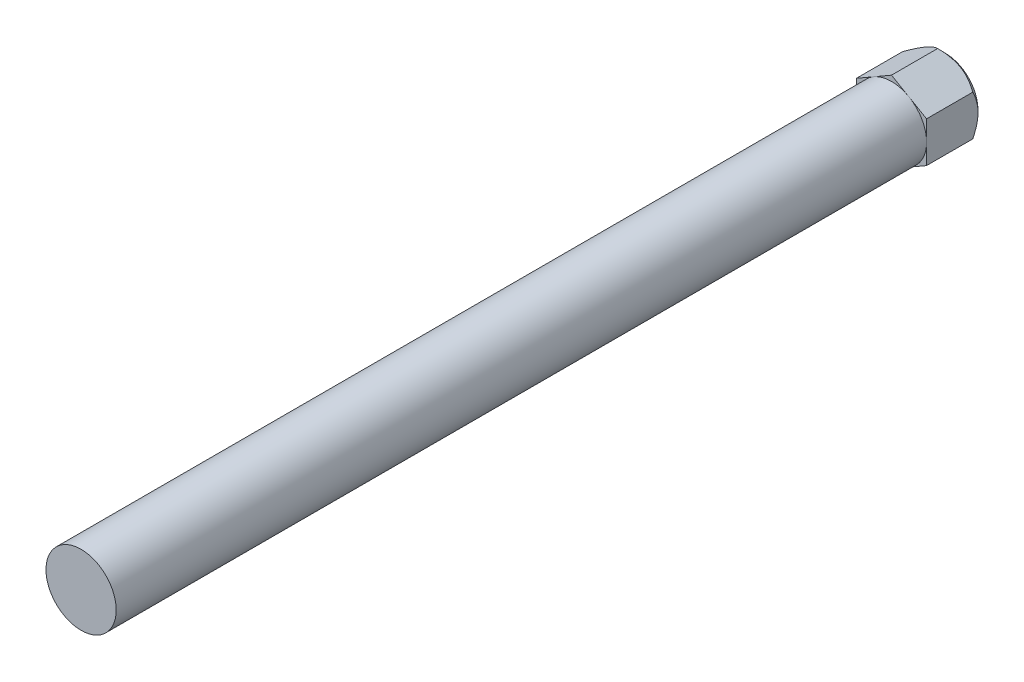
SolidWorks part; units mm, degrees
ref_plane "Front Plane" through (0, 0, 0) normal (0, 0, 1) x (1, 0, 0)
ref_plane "Top Plane" through (0, 0, 0) normal (0, 1, 0) x (1, 0, 0)
ref_plane "Right Plane" through (0, 0, 0) normal (1, 0, 0) x (0, 0, -1)
sketch "Sketch1" plane through (0, 0, 0) normal (0, 0, 1) x (1, 0, 0)
  line L1 (0, 0.15) -> (-0.1299, 0.075)
  line L2 (-0.1299, 0.075) -> (-0.1299, -0.075)
  line L3 (-0.1299, -0.075) -> (0, -0.15)
  line L4 (0, -0.15) -> (0.1299, -0.075)
  line L5 (0.1299, -0.075) -> (0.1299, 0.075)
  line L6 (0.1299, 0.075) -> (0, 0.15)
  circle A0 centre (0, 0) radius 0.1299 construction
  dimension "D1" = 0.3
extrude "Boss-Extrude1" add sketch "Sketch1" along normal blind 0.2
sketch "Sketch3" plane through (0, 0, 0) normal (1, 0, 0) x (0, 0, -1)
  line L0 (-0.2, 0) -> (49999.8, 0) construction
  line L1 (-0.2, -0.075) -> (-0.2, 0.075) construction
  line L2 (-0.1, 0.15) -> (-0.1, -49999.85) construction
  line L3 (-0.2, 0.15) -> (0, 0.15) construction
  line L4 (-0.2, -0.15) -> (0, -0.15) construction
  line L5 (-0.0289, 0.15) -> (0, 0.15)
  line L6 (0, 0.15) -> (0, 0.12)
  line L7 (0, 0.12) -> (-0.0289, 0.15)
  point P4 (-0.2, 0)
  point P10 (-0.1, 0.15)
  point P13 (-0.1, -0.15)
  dimension "D1" = 0.03
  dimension "D2" = 0.0289
sketch "Sketch5" plane through (0, 0, 0.2) normal (0, 0, 1) x (1, 0, 0)
  circle A0 centre (0, 0) radius 0.13
  dimension "D1" = 0.26
extrude "Boss-Extrude2" add sketch "Sketch5" along normal blind 3
revolve "Cut-Revolve2" cut sketch "Sketch3" angle 360 about L0
